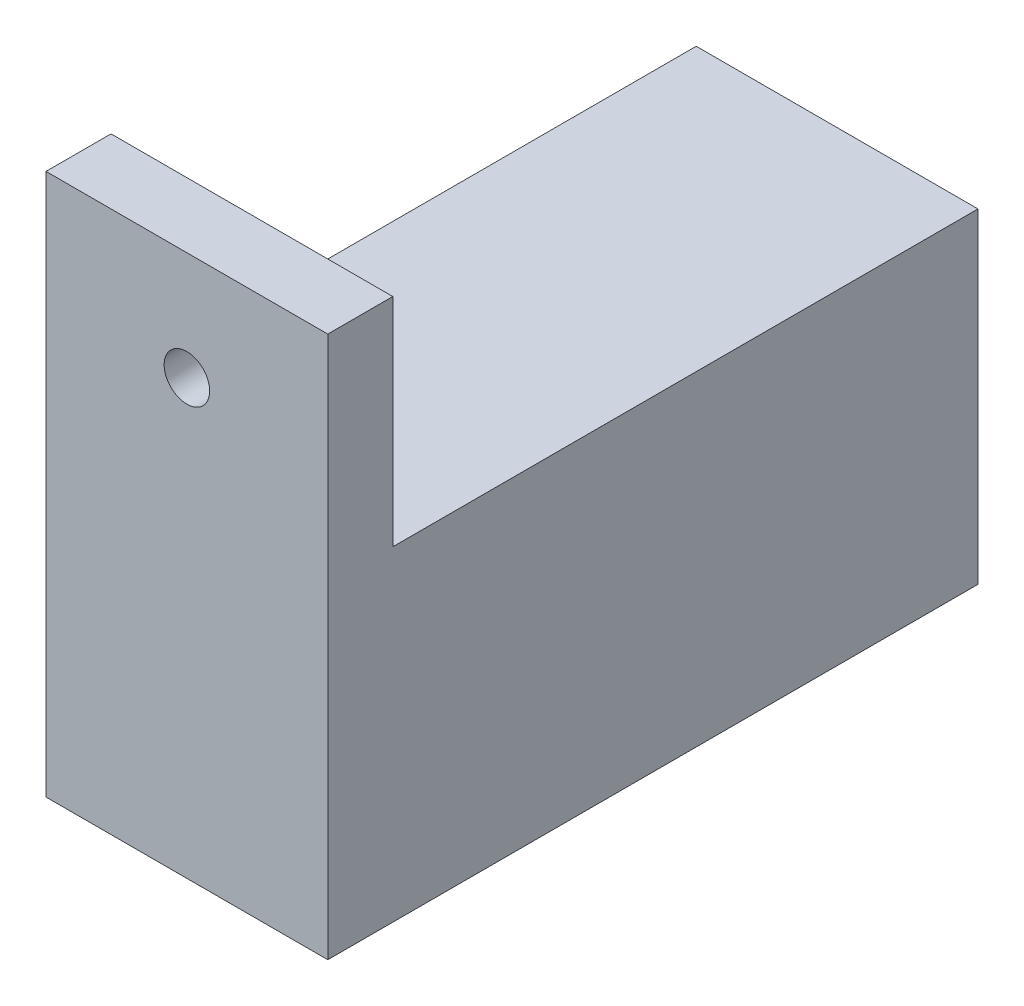
SolidWorks part; units mm, degrees
ref_plane "Front Plane" through (0, 0, 0) normal (0, 0, 1) x (1, 0, 0)
ref_plane "Top Plane" through (0, 0, 0) normal (0, 1, 0) x (1, 0, 0)
ref_plane "Right Plane" through (0, 0, 0) normal (1, 0, 0) x (0, 0, -1)
sketch "Sketch1" plane through (0, 0, 0) normal (0, 1, 0) x (1, 0, 0)
  line L1 (-36.5058, 13.4821) -> (-23.5058, 13.4821)
  line L2 (-36.5058, 13.4821) -> (-36.5058, -16.5179)
  line L3 (-36.5058, -16.5179) -> (-23.5058, -16.5179)
  line L4 (-23.5058, 13.4821) -> (-23.5058, -16.5179)
  dimension "D1" = 13
  dimension "D2" = 30
extrude "Boss-Extrude1" add sketch "Sketch1" along normal blind 15
sketch "Sketch2" plane through (0, 15, 0) normal (0, 1, 0) x (1, 0, 0)
  line L0 (-23.5058, -16.5179) -> (-23.5058, 13.4821) construction
  line L1 (-36.5058, -16.5179) -> (-23.5058, -16.5179)
  line L2 (-36.5058, -16.5179) -> (-36.5058, -13.5179)
  line L3 (-36.5058, -13.5179) -> (-23.5058, -13.5179)
  line L4 (-23.5058, -16.5179) -> (-23.5058, -13.5179)
  dimension "D1" = 3
extrude "Boss-Extrude2" add sketch "Sketch2" along normal blind 10
sketch "Sketch3" plane through (0, 0, 13.5179) normal (0, 0, -1) x (-1, 0, 0)
  line L0 (23.5058, 20) -> (36.5058, 20) construction
  line L1 (23.5058, 25) -> (23.5058, 15) construction
  line L2 (36.5058, 25) -> (36.5058, 15) construction
  line L3 (30.0058, 25) -> (30.0058, 15) construction
  line L4 (23.5058, 25) -> (36.5058, 25) construction
  line L5 (23.5058, 15) -> (36.5058, 15) construction
  circle A0 centre (30.0058, 20) radius 1.05
  dimension "D1" = 2.1
extrude "Cut-Extrude1" cut sketch "Sketch3" against normal through all
